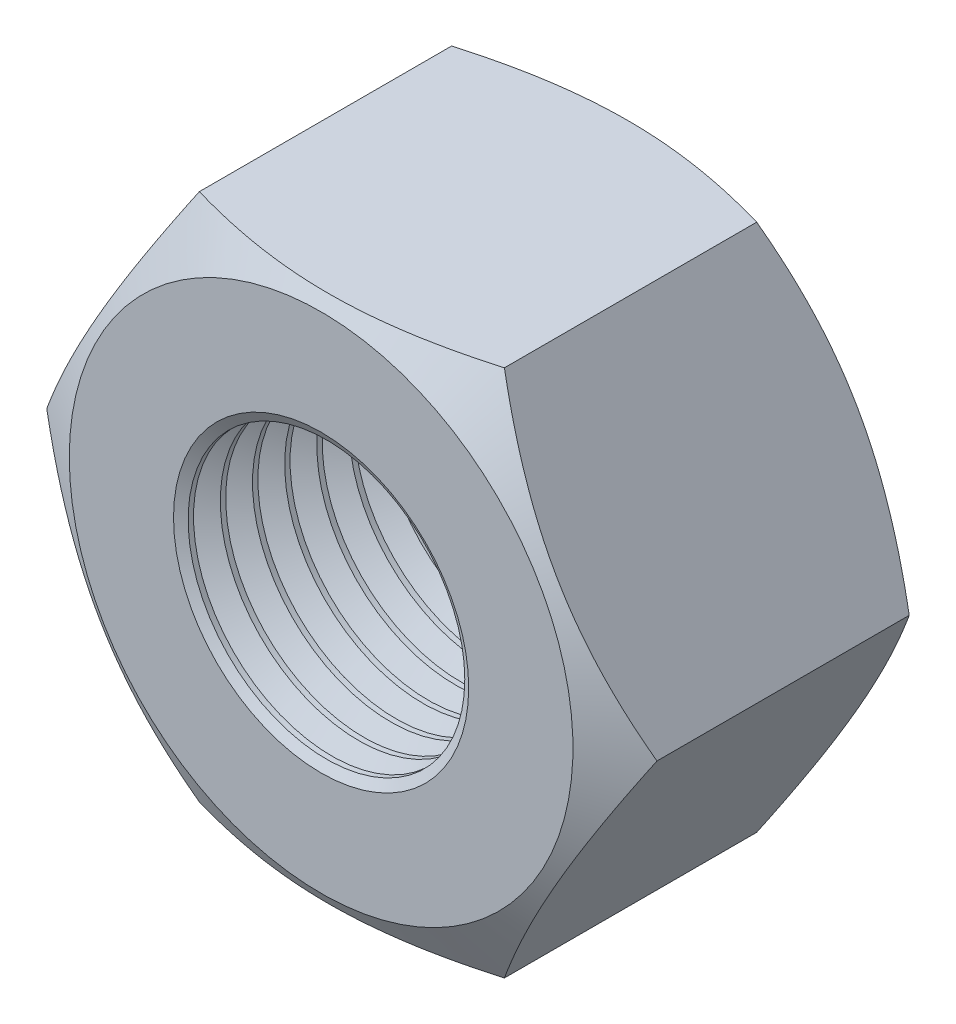
SolidWorks part; units mm, degrees
ref_plane "Front" through (0, 0, 0) normal (0, 0, 1) x (1, 0, 0)
ref_plane "Top" through (0, 0, 0) normal (0, 1, 0) x (1, 0, 0)
ref_plane "Right" through (0, 0, 0) normal (1, 0, 0) x (0, 0, -1)
sketch "Sketch1" plane through (0, 0, 0) normal (0, 0, 1) x (1, 0, 0)
  line L1 (4.6188, -8) -> (9.2376, 0)
  line L2 (9.2376, 0) -> (4.6188, 8)
  line L3 (4.6188, 8) -> (-4.6188, 8)
  line L4 (-4.6188, 8) -> (-9.2376, 0)
  line L5 (-9.2376, 0) -> (-4.6188, -8)
  line L6 (-4.6188, -8) -> (4.6188, -8)
  circle A0 centre (0, 0) radius 8 construction
  circle A1 centre (0, 0) radius 4.188
  dimension "D" = 8.376
  dimension "s" = 16
extrude "BaseNut" add sketch "Sketch1" against normal blind 9.5
cosmetic thread "ThreadCosmetic1" [suppressed] parameters "D"=10
sketch "Sketch2" plane through (0, 0, 0) normal (0, 1, 0) x (1, 0, 0)
  line L0 (-9.2376, 9.5) -> (-7.625, 9.5)
  line L2 (-7.625, 9.5) -> (-9.2376, 8.569)
  line L3 (-9.2376, 8.569) -> (-9.2376, 9.5)
  line L4 (0, 3.3759) -> (0, -9.8171) construction
  line L6 (-9.7712, 4.75) -> (9.8853, 4.75) construction
  line L7 (-9.2376, 0.931) -> (-9.2376, 0)
  line L8 (-7.625, 0) -> (-9.2376, 0.931)
  line L9 (-9.2376, 0) -> (-7.625, 0)
  line L10 (-9.2376, 9.5) -> (-9.2376, 0) construction
  dimension "dw" = 15.25
  dimension "D1" = 30
  dimension "D2" = 4.75
revolve "Double-Chamfer" cut sketch "Sketch2" angle 360 about L4
sketch "Sketch4" plane through (0, 0, 0) normal (0, 1, 0) x (1, 0, 0)
  line L0 (4.8912, 9.5) -> (4.188, 9.094)
  line L1 (4.188, 9.094) -> (3.376, 9.094)
  line L2 (3.376, 9.094) -> (3.376, 9.906)
  line L3 (3.376, 9.906) -> (4.188, 9.906)
  line L4 (4.188, 9.906) -> (4.8912, 9.5)
  line L5 (0, 0) -> (0, 109.7681) construction
  dimension "D1" = 0.812
  dimension "D2" = 8.376
revolve "Cut-Revolve10" cut sketch "Sketch4" angle 360 about L5
pattern_linear "LPattern10" count 11 spacing 0.9744 along (0, 0, 1) of "Cut-Revolve10"
equation "\"dw@Sketch2\" = \"s@Sketch1\"-0.75"
equation "\"D2@Sketch2\" = \"m@BaseNut\" / 2"
equation "\"D2@Sketch4\"=\"D@Sketch1\""
equation "\"D1@Sketch4\" =  (\"D@ThreadCosmetic1\" - \"D2@Sketch4\"  )  / 2"
equation "\"D3@LPattern10\" = \"D1@Sketch4\" * 1.2"
equation "\"D1@LPattern10\" = \"m@BaseNut\" / \"D3@LPattern10\" + 1"
